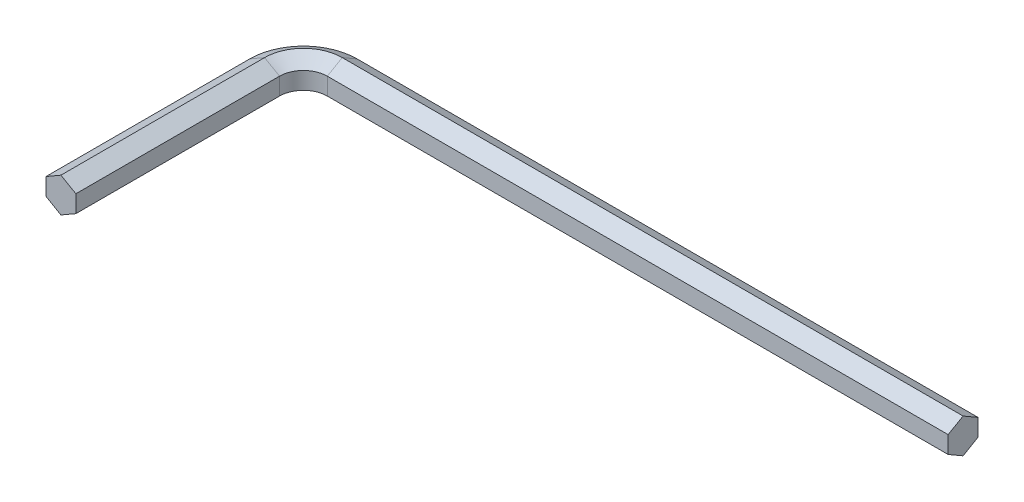
SolidWorks part; units mm, degrees
ref_plane "Front Plane" through (0, 0, 0) normal (0, 0, 1) x (1, 0, 0)
ref_plane "Top Plane" through (0, 0, 0) normal (0, 1, 0) x (1, 0, 0)
ref_plane "Right Plane" through (0, 0, 0) normal (1, 0, 0) x (0, 0, -1)
sketch "Sketch1" plane through (0, 0, 0) normal (0, 1, 0) x (1, 0, 0)
  line L0 (0, 0) -> (-51.975, 0)
  line L1 (-53.975, -2) -> (-53.975, -19.05)
  arc A0 (-51.975, 0) -> (-53.975, -2) centre (-51.975, -2) ccw
  point P6 (-53.975, 0)
  dimension "D3" = 2
  dimension "D1" = 53.975
  dimension "D2" = 19.05
sketch "Sketch2" plane through (0, 0, 0) normal (1, 0, 0) x (0, 0, -1)
  line L1 (1.25, -0.7217) -> (2.5, 0)
  line L2 (2.5, 0) -> (2.5, 1.4434)
  line L3 (2.5, 1.4434) -> (1.25, 2.1651)
  line L4 (1.25, 2.1651) -> (0, 1.4434)
  line L5 (0, 1.4434) -> (0, 0)
  line L6 (0, 0) -> (1.25, -0.7217)
  circle A0 centre (1.25, 0.7217) radius 1.25 construction
  dimension "D1" = 2.5
sweep "Sweep1" add profiles "Sketch2" path "Sketch1"
